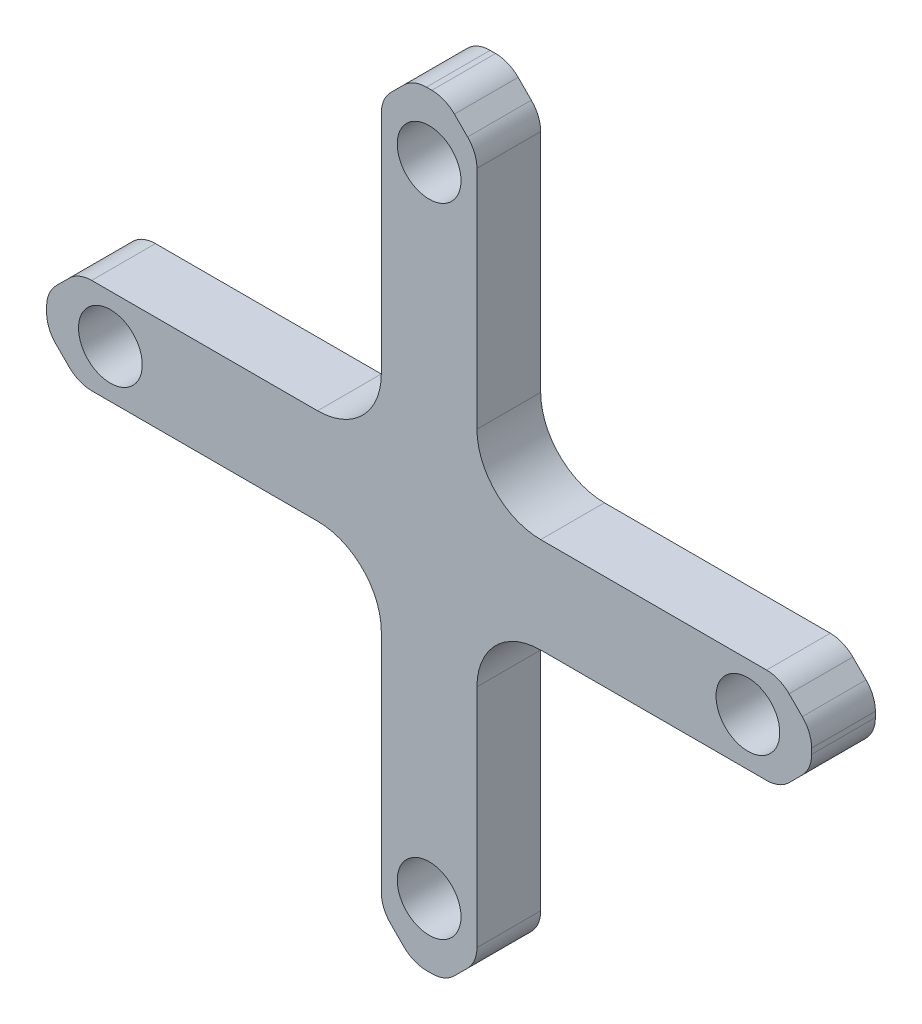
SolidWorks part; units mm, degrees
ref_plane "Спереди" through (0, 0, 0) normal (0, 0, 1) x (1, 0, 0)
ref_plane "Сверху" through (0, 0, 0) normal (0, 1, 0) x (1, 0, 0)
ref_plane "Справа" through (0, 0, 0) normal (1, 0, 0) x (0, 0, -1)
sketch "Эскиз1" plane through (0, 0, 0) normal (0, 0, 1) x (1, 0, 0)
  line L0 (1022.9849, -2.0853) -> (11.4924, -2.0853) construction
  line L1 (-3.5076, -995.4187) -> (-3.5076, -92.0853) construction
  line L2 (-993.5523, 97.9147) -> (48684.0631, 97.9147) construction
  line L3 (-993.5523, -55.8713) -> (-993.5523, 49621.7441) construction
  line L4 (-103.5076, -995.4187) -> (-103.5076, 48682.1967) construction
  line L5 (96.4924, -995.4187) -> (96.4924, 48682.1967) construction
  line L6 (-0.486, -102.0853) -> (49677.1295, -102.0853) construction
  line L7 (-15.5786, 110.8437) -> (-11.4365, 114.9858)
  line L8 (-4.3654, 117.9147) -> (-2.6497, 117.9147)
  line L9 (-18.5076, 103.7726) -> (-18.5076, 32.9147)
  line L11 (11.4924, 103.7726) -> (11.4924, 32.9147)
  line L12 (4.4214, 114.9858) -> (8.5635, 110.8437)
  line L13 (109.4214, 9.9858) -> (113.5635, 5.8437)
  line L14 (116.4924, -1.2274) -> (116.4924, -2.9431)
  line L15 (102.3503, 12.9147) -> (31.4924, 12.9147)
  line L17 (102.3503, -17.0853) -> (31.4924, -17.0853)
  line L18 (113.5635, -10.0142) -> (109.4214, -14.1563)
  line L19 (8.5635, -115.0142) -> (4.4214, -119.1563)
  line L20 (-2.6497, -122.0853) -> (-4.3654, -122.0853)
  line L21 (11.4924, -107.9431) -> (11.4924, -37.0853)
  line L23 (-18.5076, -107.9431) -> (-18.5076, -37.0853)
  line L24 (-11.4365, -119.1563) -> (-15.5786, -115.0142)
  line L25 (-116.4365, -14.1563) -> (-120.5786, -10.0142)
  line L26 (-123.5076, -2.9431) -> (-123.5076, -1.2274)
  line L27 (-109.3654, -17.0853) -> (-38.5076, -17.0853)
  line L29 (-109.3654, 12.9147) -> (-38.5076, 12.9147)
  line L30 (-120.5786, 5.8437) -> (-116.4365, 9.9858)
  line L31 (-18.5076, -2.0853) -> (-44.96, -2.0853) construction
  line L33 (-3.5076, 87.9147) -> (-3.5076, 48682.1967) construction
  arc A2 (8.5635, 110.8437) -> (11.4924, 103.7726) centre (1.4924, 103.7726) cw
  arc A3 (4.4214, 114.9858) -> (-2.6497, 117.9147) centre (-2.6497, 107.9147) ccw
  arc A4 (-15.5786, 110.8437) -> (-18.5076, 103.7726) centre (-8.5076, 103.7726) ccw
  arc A5 (-11.4365, 114.9858) -> (-4.3654, 117.9147) centre (-4.3654, 107.9147) cw
  arc A7 (109.4214, -14.1563) -> (102.3503, -17.0853) centre (102.3503, -7.0853) cw
  arc A8 (113.5635, -10.0142) -> (116.4924, -2.9431) centre (106.4924, -2.9431) ccw
  arc A9 (109.4214, 9.9858) -> (102.3503, 12.9147) centre (102.3503, 2.9147) ccw
  arc A10 (113.5635, 5.8437) -> (116.4924, -1.2274) centre (106.4924, -1.2274) cw
  arc A12 (-15.5786, -115.0142) -> (-18.5076, -107.9431) centre (-8.5076, -107.9431) cw
  arc A13 (-11.4365, -119.1563) -> (-4.3654, -122.0853) centre (-4.3654, -112.0853) ccw
  arc A14 (8.5635, -115.0142) -> (11.4924, -107.9431) centre (1.4924, -107.9431) ccw
  arc A15 (4.4214, -119.1563) -> (-2.6497, -122.0853) centre (-2.6497, -112.0853) cw
  arc A17 (-116.4365, 9.9858) -> (-109.3654, 12.9147) centre (-109.3654, 2.9147) cw
  arc A18 (-120.5786, 5.8437) -> (-123.5076, -1.2274) centre (-113.5076, -1.2274) ccw
  arc A19 (-116.4365, -14.1563) -> (-109.3654, -17.0853) centre (-109.3654, -7.0853) ccw
  arc A20 (-120.5786, -10.0142) -> (-123.5076, -2.9431) centre (-113.5076, -2.9431) cw
  arc A21 (31.4924, -17.0853) -> (11.4924, -37.0853) centre (31.4924, -37.0853) ccw
  arc A22 (31.4924, 12.9147) -> (11.4924, 32.9147) centre (31.4924, 32.9147) cw
  arc A23 (-38.5076, 12.9147) -> (-18.5076, 32.9147) centre (-38.5076, 32.9147) ccw
  arc A24 (-38.5076, -17.0853) -> (-18.5076, -37.0853) centre (-38.5076, -37.0853) cw
  circle A25 centre (-103.5076, -2.0853) radius 10
  circle A26 centre (-3.5076, 97.9147) radius 10
  circle A27 centre (96.4924, -2.0853) radius 10
  circle A28 centre (-3.5076, -102.0853) radius 10
  point P0 (-18.5076, 117.9147)
  point P17 (-3.5076, 97.9147)
  point P20 (11.4924, 117.9147)
  point P21 (-3.5076, -2.0853)
  point P29 (11.4924, 107.9147)
  point P32 (1.4924, 117.9147)
  point P35 (-18.5076, 107.9147)
  point P38 (-8.5076, 117.9147)
  point P42 (116.4924, 12.9147)
  point P45 (96.4924, -2.0853)
  point P48 (116.4924, -17.0853)
  point P61 (11.4924, -122.0853)
  point P64 (-3.5076, -102.0853)
  point P67 (-18.5076, -122.0853)
  point P80 (-123.5076, -17.0853)
  point P83 (-103.5076, -2.0853)
  point P84 (0, 0)
  point P86 (-123.5076, 12.9147)
  point P99 (-3.5076, -2.0853)
  point P107 (-3.5076, -2.0853)
  dimension "D1" = 100
  dimension "D5" = 30
  dimension "D7" = 10
  dimension "D6" = 20
  dimension "D11" = 4
  dimension "D2" = 100
  dimension "D3" = 100
  dimension "D4" = 100
  dimension "D8" = 4
extrude "Бобышка-Вытянуть3" add sketch "Эскиз1" along normal blind 20
